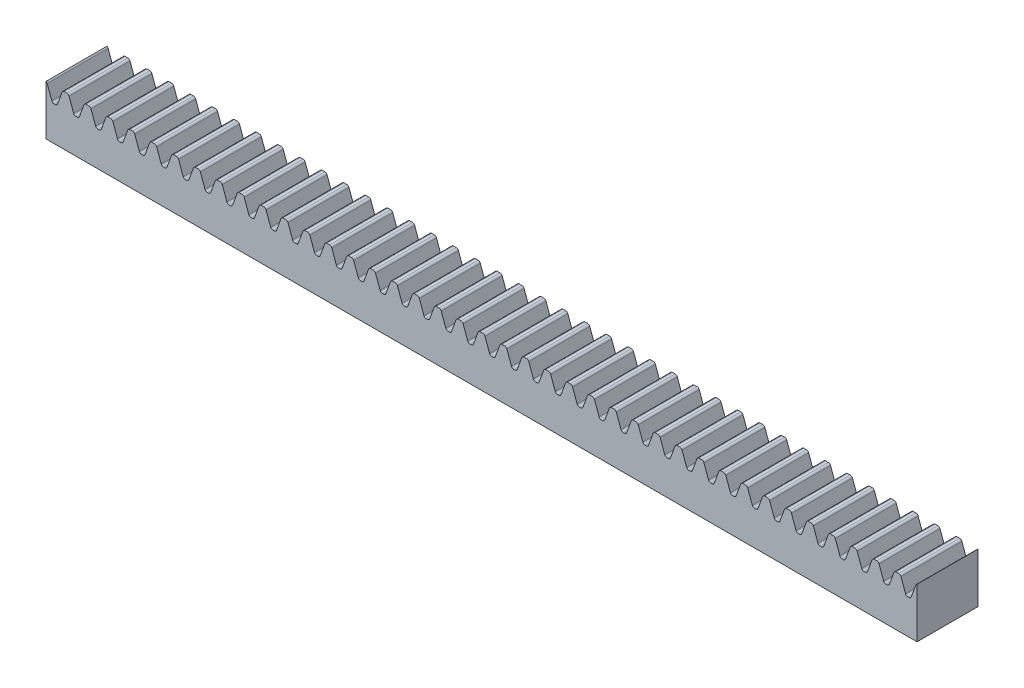
SolidWorks part; units mm, degrees
ref_plane "Front Plane" through (0, 0, 0) normal (0, 0, 1) x (1, 0, 0)
ref_plane "Top Plane" through (0, 0, 0) normal (0, 1, 0) x (1, 0, 0)
ref_plane "Right Plane" through (0, 0, 0) normal (1, 0, 0) x (0, 0, -1)
sketch "Sketch1" plane through (0, 0, 0) normal (0, 0, 1) x (1, 0, 0)
  line L0 (-50, 6.15) -> (-50, -6.15) construction
  line L1 (-50, -6.15) -> (50, -6.15) construction
  line L2 (50, -6.15) -> (50, 6.15) construction
  line L4 (0, 6.15) -> (0, -6.15) construction
  line L5 (-50, 5.35) -> (50, 5.35) construction
  line L6 (-48.0894, 6.15) -> (-47.4151, 6.15) construction
  line L7 (-47.4151, 6.15) -> (-46.7599, 4.35) construction
  line L8 (-48.0894, 6.15) -> (-48.7445, 4.35) construction
  line L9 (-48.7445, 4.35) -> (-46.7599, 4.35) construction
  line L10 (-47.7522, 6.15) -> (-47.7522, 4.35) construction
  line L11 (-50, 0) -> (-42.7257, 0) construction
  line L12 (50, 0) -> (42.7257, 0) construction
  point P15 (-45.2389, 6.15)
  point P16 (-19.5, -6.15)
  point P17 (-47.1239, 5.35)
  point P18 (-48.3805, 5.35)
  point P21 (-0.4, -6.15)
  dimension "Length" = 100
  dimension "Height" = 12.3
  dimension "Approximate Number of Teeth" = 39
  dimension "Pressure Angle" = 20
  dimension "Circular Pitch" = 2.5133
  dimension "Addendum" = 0.8
  dimension "Dedendum" = 1
  dimension "Circular Tooth Thickness" = 1.2566
  dimension "Module" = 0.8
  dimension "Rack Length" = 95.5044
  dimension "D1" = 5.0265
sketch "Sketch2" plane through (0, 0, 0) normal (1, 0, 0) x (0, 0, -1)
  line L0 (-4, 0) -> (4, 0) construction
  dimension "Face Width" = 8
sketch "Sketch3" plane through (0, 0, 0) normal (0, 0, 1) x (1, 0, 0)
  line L1 (-50, 6.15) -> (50, 6.15)
  line L2 (-50, 6.15) -> (-50, -6.15)
  line L3 (-50, -6.15) -> (50, -6.15)
  line L4 (50, 6.15) -> (50, -6.15)
extrude "Boss-Extrude1" add sketch "Sketch3" against normal up to vertex (4 mm away) and the other way up to vertex (4 mm away) up to point (0, 0, -4) other way up to point (0, 0, 4)
sketch "Sketch4" plane through (0, 0, 0) normal (0, 0, 1) x (1, 0, 0)
  line L0 (-47.7522, 6.15) -> (-45.2389, 6.15) construction
  line L9 (-46.4956, 6.15) -> (-46.4956, 4.35)
  line L10 (-46.4956, 4.35) -> (-46.7599, 4.35)
  line L11 (-46.7599, 4.35) -> (-47.4151, 6.15)
  line L12 (-47.4151, 6.15) -> (-46.4956, 6.15)
  line L13 (-48.0894, 6.15) -> (-48.7445, 4.35)
  line L14 (-48.7445, 4.35) -> (-49.0088, 4.35)
  line L15 (-49.0088, 4.35) -> (-49.0088, 6.15)
  line L16 (-49.0088, 6.15) -> (-48.0894, 6.15)
  line L17 (50, 6.15) -> (-50, 6.15) construction
  line L18 (-48.0894, 6.15) -> (-47.9014, 6.15)
  line L19 (-47.603, 6.15) -> (-47.4151, 6.15)
  arc A0 (-48.9324, 4.35) -> (-48.6802, 4.5266) centre (-48.9324, 4.6184) ccw
  arc A1 (-46.8242, 4.5266) -> (-46.572, 4.35) centre (-46.572, 4.6184) ccw
  arc A2 (-48.1536, 5.9734) -> (-47.9014, 6.15) centre (-47.9014, 5.8816) cw
  arc A3 (-47.603, 6.15) -> (-47.3508, 5.9734) centre (-47.603, 5.8816) cw
  dimension "D1" = 0.2684
extrude "Cut-Extrude1" cut sketch "Sketch4" against normal through all both and the other way through all contours L14 A0 L13 L16 L15 | L13 A2 L18 | L19 A3 L11 | L11 A1 L10 L9 L12
pattern_linear "LPattern1" count 40 spacing 2.5133 along (1, 0, 0) count 2 spacing 2.5133 along (-1, 0, 0) of "Cut-Extrude1"
sketch "Drawing Refernce 1" plane through (0, 0, 4) normal (0, 0, 1) x (1, 0, 0)
  line L0 (-50, 0) -> (50, 0) construction
  point P6 (-35, 0)
  point P7 (-27.5, 0)
  point P8 (35, 0)
  dimension "D1" = 15
  dimension "D2" = 22.5
  dimension "D3" = 15
sketch "Sketch5" plane through (0, -6.15, 0) normal (0, -1, 0) x (1, 0, 0)
  line L1 (-50, 4) -> (50, 4)
  line L2 (-50, 4) -> (-50, -4)
  line L3 (-50, -4) -> (50, -4)
  line L4 (50, 4) -> (50, -4)
extrude "Cut-Extrude2" cut sketch "Sketch5" against normal blind 6.55
sketch "Sketch6" plane through (0, 0, -4) normal (0, 0, -1) x (-1, 0, 0)
  line L162 (-50, 0.4) -> (50, 0.4)
  line L163 (50, 0.4) -> (50, 6.1235)
  line L164 (49.8641, 5.9734) -> (49.3375, 4.5266)
  line L165 (49.0853, 4.35) -> (48.9324, 4.35)
  line L166 (48.6802, 4.5266) -> (48.1536, 5.9734)
  line L167 (47.9014, 6.15) -> (47.603, 6.15)
  line L168 (47.3508, 5.9734) -> (46.8242, 4.5266)
  line L169 (46.572, 4.35) -> (46.4192, 4.35)
  line L170 (46.1669, 4.5266) -> (45.6404, 5.9734)
  line L171 (45.3881, 6.15) -> (45.0897, 6.15)
  line L172 (44.8375, 5.9734) -> (44.3109, 4.5266)
  line L173 (44.0587, 4.35) -> (43.9059, 4.35)
  line L174 (43.6537, 4.5266) -> (43.1271, 5.9734)
  line L175 (42.8749, 6.15) -> (42.5765, 6.15)
  line L176 (42.3242, 5.9734) -> (41.7977, 4.5266)
  line L177 (41.5454, 4.35) -> (41.3926, 4.35)
  line L178 (41.1404, 4.5266) -> (40.6138, 5.9734)
  line L179 (40.3616, 6.15) -> (40.0632, 6.15)
  line L180 (39.811, 5.9734) -> (39.2844, 4.5266)
  line L181 (39.0322, 4.35) -> (38.8793, 4.35)
  line L182 (38.6271, 4.5266) -> (38.1005, 5.9734)
  line L183 (37.8483, 6.15) -> (37.5499, 6.15)
  line L184 (37.2977, 5.9734) -> (36.7711, 4.5266)
  line L185 (36.5189, 4.35) -> (36.3661, 4.35)
  line L186 (36.1138, 4.5266) -> (35.5873, 5.9734)
  line L187 (35.335, 6.15) -> (35.0366, 6.15)
  line L188 (34.7844, 5.9734) -> (34.2578, 4.5266)
  line L189 (34.0056, 4.35) -> (33.8528, 4.35)
  line L190 (33.6006, 4.5266) -> (33.074, 5.9734)
  line L191 (32.8218, 6.15) -> (32.5234, 6.15)
  line L192 (32.2711, 5.9734) -> (31.7446, 4.5266)
  line L193 (31.4923, 4.35) -> (31.3395, 4.35)
  line L194 (31.0873, 4.5266) -> (30.5607, 5.9734)
  line L195 (30.3085, 6.15) -> (30.0101, 6.15)
  line L196 (29.7579, 5.9734) -> (29.2313, 4.5266)
  line L197 (28.9791, 4.35) -> (28.8262, 4.35)
  line L198 (28.574, 4.5266) -> (28.0474, 5.9734)
  line L199 (27.7952, 6.15) -> (27.4968, 6.15)
  line L200 (27.2446, 5.9734) -> (26.718, 4.5266)
  line L201 (26.4658, 4.35) -> (26.313, 4.35)
  line L202 (26.0608, 4.5266) -> (25.5342, 5.9734)
  line L203 (25.2819, 6.15) -> (24.9835, 6.15)
  line L204 (24.7313, 5.9734) -> (24.2047, 4.5266)
  line L205 (23.9525, 4.35) -> (23.7997, 4.35)
  line L206 (23.5475, 4.5266) -> (23.0209, 5.9734)
  line L207 (22.7687, 6.15) -> (22.4703, 6.15)
  line L208 (22.218, 5.9734) -> (21.6915, 4.5266)
  line L209 (21.4392, 4.35) -> (21.2864, 4.35)
  line L210 (21.0342, 4.5266) -> (20.5076, 5.9734)
  line L211 (20.2554, 6.15) -> (19.957, 6.15)
  line L212 (19.7048, 5.9734) -> (19.1782, 4.5266)
  line L213 (18.926, 4.35) -> (18.7731, 4.35)
  line L214 (18.5209, 4.5266) -> (17.9943, 5.9734)
  line L215 (17.7421, 6.15) -> (17.4437, 6.15)
  line L216 (17.1915, 5.9734) -> (16.6649, 4.5266)
  line L217 (16.4127, 4.35) -> (16.2599, 4.35)
  line L218 (16.0077, 4.5266) -> (15.4811, 5.9734)
  line L219 (15.2288, 6.15) -> (14.9304, 6.15)
  line L220 (14.6782, 5.9734) -> (14.1516, 4.5266)
  line L221 (13.8994, 4.35) -> (13.7466, 4.35)
  line L222 (13.4944, 4.5266) -> (12.9678, 5.9734)
  line L223 (12.7156, 6.15) -> (12.4172, 6.15)
  line L224 (12.1649, 5.9734) -> (11.6384, 4.5266)
  line L225 (11.3861, 4.35) -> (11.2333, 4.35)
  line L226 (10.9811, 4.5266) -> (10.4545, 5.9734)
  line L227 (10.2023, 6.15) -> (9.9039, 6.15)
  line L228 (9.6517, 5.9734) -> (9.1251, 4.5266)
  line L229 (8.8729, 4.35) -> (8.72, 4.35)
  line L230 (8.4678, 4.5266) -> (7.9412, 5.9734)
  line L231 (7.689, 6.15) -> (7.3906, 6.15)
  line L232 (7.1384, 5.9734) -> (6.6118, 4.5266)
  line L233 (6.3596, 4.35) -> (6.2068, 4.35)
  line L234 (5.9546, 4.5266) -> (5.428, 5.9734)
  line L235 (5.1758, 6.15) -> (4.8773, 6.15)
  line L236 (4.6251, 5.9734) -> (4.0985, 4.5266)
  line L237 (3.8463, 4.35) -> (3.6935, 4.35)
  line L238 (3.4413, 4.5266) -> (2.9147, 5.9734)
  line L239 (2.6625, 6.15) -> (2.3641, 6.15)
  line L240 (2.1119, 5.9734) -> (1.5853, 4.5266)
  line L241 (1.333, 4.35) -> (1.1802, 4.35)
  line L242 (0.928, 4.5266) -> (0.4014, 5.9734)
  line L243 (0.1492, 6.15) -> (-0.1492, 6.15)
  line L244 (-0.4014, 5.9734) -> (-0.928, 4.5266)
  line L245 (-1.1802, 4.35) -> (-1.333, 4.35)
  line L246 (-1.5853, 4.5266) -> (-2.1119, 5.9734)
  line L247 (-2.3641, 6.15) -> (-2.6625, 6.15)
  line L248 (-2.9147, 5.9734) -> (-3.4413, 4.5266)
  line L249 (-3.6935, 4.35) -> (-3.8463, 4.35)
  line L250 (-4.0985, 4.5266) -> (-4.6251, 5.9734)
  line L251 (-4.8773, 6.15) -> (-5.1758, 6.15)
  line L252 (-5.428, 5.9734) -> (-5.9546, 4.5266)
  line L253 (-6.2068, 4.35) -> (-6.3596, 4.35)
  line L254 (-6.6118, 4.5266) -> (-7.1384, 5.9734)
  line L255 (-7.3906, 6.15) -> (-7.689, 6.15)
  line L256 (-7.9412, 5.9734) -> (-8.4678, 4.5266)
  line L257 (-8.72, 4.35) -> (-8.8729, 4.35)
  line L258 (-9.1251, 4.5266) -> (-9.6517, 5.9734)
  line L259 (-9.9039, 6.15) -> (-10.2023, 6.15)
  line L260 (-10.4545, 5.9734) -> (-10.9811, 4.5266)
  line L261 (-11.2333, 4.35) -> (-11.3861, 4.35)
  line L262 (-11.6384, 4.5266) -> (-12.1649, 5.9734)
  line L263 (-12.4172, 6.15) -> (-12.7156, 6.15)
  line L264 (-12.9678, 5.9734) -> (-13.4944, 4.5266)
  line L265 (-13.7466, 4.35) -> (-13.8994, 4.35)
  line L266 (-14.1516, 4.5266) -> (-14.6782, 5.9734)
  line L267 (-14.9304, 6.15) -> (-15.2288, 6.15)
  line L268 (-15.4811, 5.9734) -> (-16.0077, 4.5266)
  line L269 (-16.2599, 4.35) -> (-16.4127, 4.35)
  line L270 (-16.6649, 4.5266) -> (-17.1915, 5.9734)
  line L271 (-17.4437, 6.15) -> (-17.7421, 6.15)
  line L272 (-17.9943, 5.9734) -> (-18.5209, 4.5266)
  line L273 (-18.7731, 4.35) -> (-18.926, 4.35)
  line L274 (-19.1782, 4.5266) -> (-19.7048, 5.9734)
  line L275 (-19.957, 6.15) -> (-20.2554, 6.15)
  line L276 (-20.5076, 5.9734) -> (-21.0342, 4.5266)
  line L277 (-21.2864, 4.35) -> (-21.4392, 4.35)
  line L278 (-21.6915, 4.5266) -> (-22.218, 5.9734)
  line L279 (-22.4703, 6.15) -> (-22.7687, 6.15)
  line L280 (-23.0209, 5.9734) -> (-23.5475, 4.5266)
  line L281 (-23.7997, 4.35) -> (-23.9525, 4.35)
  line L282 (-24.2047, 4.5266) -> (-24.7313, 5.9734)
  line L283 (-24.9835, 6.15) -> (-25.2819, 6.15)
  line L284 (-25.5342, 5.9734) -> (-26.0608, 4.5266)
  line L285 (-26.313, 4.35) -> (-26.4658, 4.35)
  line L286 (-26.718, 4.5266) -> (-27.2446, 5.9734)
  line L287 (-27.4968, 6.15) -> (-27.7952, 6.15)
  line L288 (-28.0474, 5.9734) -> (-28.574, 4.5266)
  line L289 (-28.8262, 4.35) -> (-28.9791, 4.35)
  line L290 (-29.2313, 4.5266) -> (-29.7579, 5.9734)
  line L291 (-30.0101, 6.15) -> (-30.3085, 6.15)
  line L292 (-30.5607, 5.9734) -> (-31.0873, 4.5266)
  line L293 (-31.3395, 4.35) -> (-31.4923, 4.35)
  line L294 (-31.7446, 4.5266) -> (-32.2711, 5.9734)
  line L295 (-32.5234, 6.15) -> (-32.8218, 6.15)
  line L296 (-33.074, 5.9734) -> (-33.6006, 4.5266)
  line L297 (-33.8528, 4.35) -> (-34.0056, 4.35)
  line L298 (-34.2578, 4.5266) -> (-34.7844, 5.9734)
  line L299 (-35.0366, 6.15) -> (-35.335, 6.15)
  line L300 (-35.5873, 5.9734) -> (-36.1138, 4.5266)
  line L301 (-36.3661, 4.35) -> (-36.5189, 4.35)
  line L302 (-36.7711, 4.5266) -> (-37.2977, 5.9734)
  line L303 (-37.5499, 6.15) -> (-37.8483, 6.15)
  line L304 (-38.1005, 5.9734) -> (-38.6271, 4.5266)
  line L305 (-38.8793, 4.35) -> (-39.0322, 4.35)
  line L306 (-39.2844, 4.5266) -> (-39.811, 5.9734)
  line L307 (-40.0632, 6.15) -> (-40.3616, 6.15)
  line L308 (-40.6138, 5.9734) -> (-41.1404, 4.5266)
  line L309 (-41.3926, 4.35) -> (-41.5454, 4.35)
  line L310 (-41.7977, 4.5266) -> (-42.3242, 5.9734)
  line L311 (-42.5765, 6.15) -> (-42.8749, 6.15)
  line L312 (-43.1271, 5.9734) -> (-43.6537, 4.5266)
  line L313 (-43.9059, 4.35) -> (-44.0587, 4.35)
  line L314 (-44.3109, 4.5266) -> (-44.8375, 5.9734)
  line L315 (-45.0897, 6.15) -> (-45.3881, 6.15)
  line L316 (-45.6404, 5.9734) -> (-46.1669, 4.5266)
  line L317 (-46.4192, 4.35) -> (-46.572, 4.35)
  line L318 (-46.8242, 4.5266) -> (-47.3508, 5.9734)
  line L319 (-47.603, 6.15) -> (-47.9014, 6.15)
  line L320 (-48.1536, 5.9734) -> (-48.6802, 4.5266)
  line L321 (-48.9324, 4.35) -> (-49.0853, 4.35)
  line L322 (-49.3375, 4.5266) -> (-49.8641, 5.9734)
  line L323 (-50, 6.1235) -> (-50, 0.4)
  line L324 (-50, 0.4) -> (50, 0.4)
  line L325 (50, 0.4) -> (50, 6.1235)
  line L326 (49.8641, 5.9734) -> (49.3375, 4.5266)
  line L327 (49.0853, 4.35) -> (48.9324, 4.35)
  line L328 (48.6802, 4.5266) -> (48.1536, 5.9734)
  line L329 (47.9014, 6.15) -> (47.603, 6.15)
  line L330 (47.3508, 5.9734) -> (46.8242, 4.5266)
  line L331 (46.572, 4.35) -> (46.4192, 4.35)
  line L332 (46.1669, 4.5266) -> (45.6404, 5.9734)
  line L333 (45.3881, 6.15) -> (45.0897, 6.15)
  line L334 (44.8375, 5.9734) -> (44.3109, 4.5266)
  line L335 (44.0587, 4.35) -> (43.9059, 4.35)
  line L336 (43.6537, 4.5266) -> (43.1271, 5.9734)
  line L337 (42.8749, 6.15) -> (42.5765, 6.15)
  line L338 (42.3242, 5.9734) -> (41.7977, 4.5266)
  line L339 (41.5454, 4.35) -> (41.3926, 4.35)
  line L340 (41.1404, 4.5266) -> (40.6138, 5.9734)
  line L341 (40.3616, 6.15) -> (40.0632, 6.15)
  line L342 (39.811, 5.9734) -> (39.2844, 4.5266)
  line L343 (39.0322, 4.35) -> (38.8793, 4.35)
  line L344 (38.6271, 4.5266) -> (38.1005, 5.9734)
  line L345 (37.8483, 6.15) -> (37.5499, 6.15)
  line L346 (37.2977, 5.9734) -> (36.7711, 4.5266)
  line L347 (36.5189, 4.35) -> (36.3661, 4.35)
  line L348 (36.1138, 4.5266) -> (35.5873, 5.9734)
  line L349 (35.335, 6.15) -> (35.0366, 6.15)
  line L350 (34.7844, 5.9734) -> (34.2578, 4.5266)
  line L351 (34.0056, 4.35) -> (33.8528, 4.35)
  line L352 (33.6006, 4.5266) -> (33.074, 5.9734)
  line L353 (32.8218, 6.15) -> (32.5234, 6.15)
  line L354 (32.2711, 5.9734) -> (31.7446, 4.5266)
  line L355 (31.4923, 4.35) -> (31.3395, 4.35)
  line L356 (31.0873, 4.5266) -> (30.5607, 5.9734)
  line L357 (30.3085, 6.15) -> (30.0101, 6.15)
  line L358 (29.7579, 5.9734) -> (29.2313, 4.5266)
  line L359 (28.9791, 4.35) -> (28.8262, 4.35)
  line L360 (28.574, 4.5266) -> (28.0474, 5.9734)
  line L361 (27.7952, 6.15) -> (27.4968, 6.15)
  line L362 (27.2446, 5.9734) -> (26.718, 4.5266)
  line L363 (26.4658, 4.35) -> (26.313, 4.35)
  line L364 (26.0608, 4.5266) -> (25.5342, 5.9734)
  line L365 (25.2819, 6.15) -> (24.9835, 6.15)
  line L366 (24.7313, 5.9734) -> (24.2047, 4.5266)
  line L367 (23.9525, 4.35) -> (23.7997, 4.35)
  line L368 (23.5475, 4.5266) -> (23.0209, 5.9734)
  line L369 (22.7687, 6.15) -> (22.4703, 6.15)
  line L370 (22.218, 5.9734) -> (21.6915, 4.5266)
  line L371 (21.4392, 4.35) -> (21.2864, 4.35)
  line L372 (21.0342, 4.5266) -> (20.5076, 5.9734)
  line L373 (20.2554, 6.15) -> (19.957, 6.15)
  line L374 (19.7048, 5.9734) -> (19.1782, 4.5266)
  line L375 (18.926, 4.35) -> (18.7731, 4.35)
  line L376 (18.5209, 4.5266) -> (17.9943, 5.9734)
  line L377 (17.7421, 6.15) -> (17.4437, 6.15)
  line L378 (17.1915, 5.9734) -> (16.6649, 4.5266)
  line L379 (16.4127, 4.35) -> (16.2599, 4.35)
  line L380 (16.0077, 4.5266) -> (15.4811, 5.9734)
  line L381 (15.2288, 6.15) -> (14.9304, 6.15)
  line L382 (14.6782, 5.9734) -> (14.1516, 4.5266)
  line L383 (13.8994, 4.35) -> (13.7466, 4.35)
  line L384 (13.4944, 4.5266) -> (12.9678, 5.9734)
  line L385 (12.7156, 6.15) -> (12.4172, 6.15)
  line L386 (12.1649, 5.9734) -> (11.6384, 4.5266)
  line L387 (11.3861, 4.35) -> (11.2333, 4.35)
  line L388 (10.9811, 4.5266) -> (10.4545, 5.9734)
  line L389 (10.2023, 6.15) -> (9.9039, 6.15)
  line L390 (9.6517, 5.9734) -> (9.1251, 4.5266)
  line L391 (8.8729, 4.35) -> (8.72, 4.35)
  line L392 (8.4678, 4.5266) -> (7.9412, 5.9734)
  line L393 (7.689, 6.15) -> (7.3906, 6.15)
  line L394 (7.1384, 5.9734) -> (6.6118, 4.5266)
  line L395 (6.3596, 4.35) -> (6.2068, 4.35)
  line L396 (5.9546, 4.5266) -> (5.428, 5.9734)
  line L397 (5.1758, 6.15) -> (4.8773, 6.15)
  line L398 (4.6251, 5.9734) -> (4.0985, 4.5266)
  line L399 (3.8463, 4.35) -> (3.6935, 4.35)
  line L400 (3.4413, 4.5266) -> (2.9147, 5.9734)
  line L401 (2.6625, 6.15) -> (2.3641, 6.15)
  line L402 (2.1119, 5.9734) -> (1.5853, 4.5266)
  line L403 (1.333, 4.35) -> (1.1802, 4.35)
  line L404 (0.928, 4.5266) -> (0.4014, 5.9734)
  line L405 (0.1492, 6.15) -> (-0.1492, 6.15)
  line L406 (-0.4014, 5.9734) -> (-0.928, 4.5266)
  line L407 (-1.1802, 4.35) -> (-1.333, 4.35)
  line L408 (-1.5853, 4.5266) -> (-2.1119, 5.9734)
  line L409 (-2.3641, 6.15) -> (-2.6625, 6.15)
  line L410 (-2.9147, 5.9734) -> (-3.4413, 4.5266)
  line L411 (-3.6935, 4.35) -> (-3.8463, 4.35)
  line L412 (-4.0985, 4.5266) -> (-4.6251, 5.9734)
  line L413 (-4.8773, 6.15) -> (-5.1758, 6.15)
  line L414 (-5.428, 5.9734) -> (-5.9546, 4.5266)
  line L415 (-6.2068, 4.35) -> (-6.3596, 4.35)
  line L416 (-6.6118, 4.5266) -> (-7.1384, 5.9734)
  line L417 (-7.3906, 6.15) -> (-7.689, 6.15)
  line L418 (-7.9412, 5.9734) -> (-8.4678, 4.5266)
  line L419 (-8.72, 4.35) -> (-8.8729, 4.35)
  line L420 (-9.1251, 4.5266) -> (-9.6517, 5.9734)
  line L421 (-9.9039, 6.15) -> (-10.2023, 6.15)
  line L422 (-10.4545, 5.9734) -> (-10.9811, 4.5266)
  line L423 (-11.2333, 4.35) -> (-11.3861, 4.35)
  line L424 (-11.6384, 4.5266) -> (-12.1649, 5.9734)
  line L425 (-12.4172, 6.15) -> (-12.7156, 6.15)
  line L426 (-12.9678, 5.9734) -> (-13.4944, 4.5266)
  line L427 (-13.7466, 4.35) -> (-13.8994, 4.35)
  line L428 (-14.1516, 4.5266) -> (-14.6782, 5.9734)
  line L429 (-14.9304, 6.15) -> (-15.2288, 6.15)
  line L430 (-15.4811, 5.9734) -> (-16.0077, 4.5266)
  line L431 (-16.2599, 4.35) -> (-16.4127, 4.35)
  line L432 (-16.6649, 4.5266) -> (-17.1915, 5.9734)
  line L433 (-17.4437, 6.15) -> (-17.7421, 6.15)
  line L434 (-17.9943, 5.9734) -> (-18.5209, 4.5266)
  line L435 (-18.7731, 4.35) -> (-18.926, 4.35)
  line L436 (-19.1782, 4.5266) -> (-19.7048, 5.9734)
  line L437 (-19.957, 6.15) -> (-20.2554, 6.15)
  line L438 (-20.5076, 5.9734) -> (-21.0342, 4.5266)
  line L439 (-21.2864, 4.35) -> (-21.4392, 4.35)
  line L440 (-21.6915, 4.5266) -> (-22.218, 5.9734)
  line L441 (-22.4703, 6.15) -> (-22.7687, 6.15)
  line L442 (-23.0209, 5.9734) -> (-23.5475, 4.5266)
  line L443 (-23.7997, 4.35) -> (-23.9525, 4.35)
  line L444 (-24.2047, 4.5266) -> (-24.7313, 5.9734)
  line L445 (-24.9835, 6.15) -> (-25.2819, 6.15)
  line L446 (-25.5342, 5.9734) -> (-26.0608, 4.5266)
  line L447 (-26.313, 4.35) -> (-26.4658, 4.35)
  line L448 (-26.718, 4.5266) -> (-27.2446, 5.9734)
  line L449 (-27.4968, 6.15) -> (-27.7952, 6.15)
  line L450 (-28.0474, 5.9734) -> (-28.574, 4.5266)
  line L451 (-28.8262, 4.35) -> (-28.9791, 4.35)
  line L452 (-29.2313, 4.5266) -> (-29.7579, 5.9734)
  line L453 (-30.0101, 6.15) -> (-30.3085, 6.15)
  line L454 (-30.5607, 5.9734) -> (-31.0873, 4.5266)
  line L455 (-31.3395, 4.35) -> (-31.4923, 4.35)
  line L456 (-31.7446, 4.5266) -> (-32.2711, 5.9734)
  line L457 (-32.5234, 6.15) -> (-32.8218, 6.15)
  line L458 (-33.074, 5.9734) -> (-33.6006, 4.5266)
  line L459 (-33.8528, 4.35) -> (-34.0056, 4.35)
  line L460 (-34.2578, 4.5266) -> (-34.7844, 5.9734)
  line L461 (-35.0366, 6.15) -> (-35.335, 6.15)
  line L462 (-35.5873, 5.9734) -> (-36.1138, 4.5266)
  line L463 (-36.3661, 4.35) -> (-36.5189, 4.35)
  line L464 (-36.7711, 4.5266) -> (-37.2977, 5.9734)
  line L465 (-37.5499, 6.15) -> (-37.8483, 6.15)
  line L466 (-38.1005, 5.9734) -> (-38.6271, 4.5266)
  line L467 (-38.8793, 4.35) -> (-39.0322, 4.35)
  line L468 (-39.2844, 4.5266) -> (-39.811, 5.9734)
  line L469 (-40.0632, 6.15) -> (-40.3616, 6.15)
  line L470 (-40.6138, 5.9734) -> (-41.1404, 4.5266)
  line L471 (-41.3926, 4.35) -> (-41.5454, 4.35)
  line L472 (-41.7977, 4.5266) -> (-42.3242, 5.9734)
  line L473 (-42.5765, 6.15) -> (-42.8749, 6.15)
  line L474 (-43.1271, 5.9734) -> (-43.6537, 4.5266)
  line L475 (-43.9059, 4.35) -> (-44.0587, 4.35)
  line L476 (-44.3109, 4.5266) -> (-44.8375, 5.9734)
  line L477 (-45.0897, 6.15) -> (-45.3881, 6.15)
  line L478 (-45.6404, 5.9734) -> (-46.1669, 4.5266)
  line L479 (-46.4192, 4.35) -> (-46.572, 4.35)
  line L480 (-46.8242, 4.5266) -> (-47.3508, 5.9734)
  line L481 (-47.603, 6.15) -> (-47.9014, 6.15)
  line L482 (-48.1536, 5.9734) -> (-48.6802, 4.5266)
  line L483 (-48.9324, 4.35) -> (-49.0853, 4.35)
  line L484 (-49.3375, 4.5266) -> (-49.8641, 5.9734)
  line L485 (-50, 6.1235) -> (-50, 0.4)
  arc A160 (50, 6.1235) -> (49.8641, 5.9734) centre (50.1163, 5.8816) ccw
  arc A161 (49.0853, 4.35) -> (49.3375, 4.5266) centre (49.0853, 4.6184) ccw
  arc A162 (48.6802, 4.5266) -> (48.9324, 4.35) centre (48.9324, 4.6184) ccw
  arc A163 (48.1536, 5.9734) -> (47.9014, 6.15) centre (47.9014, 5.8816) ccw
  arc A164 (47.603, 6.15) -> (47.3508, 5.9734) centre (47.603, 5.8816) ccw
  arc A165 (46.572, 4.35) -> (46.8242, 4.5266) centre (46.572, 4.6184) ccw
  arc A166 (46.1669, 4.5266) -> (46.4192, 4.35) centre (46.4192, 4.6184) ccw
  arc A167 (45.6404, 5.9734) -> (45.3881, 6.15) centre (45.3881, 5.8816) ccw
  arc A168 (45.0897, 6.15) -> (44.8375, 5.9734) centre (45.0897, 5.8816) ccw
  arc A169 (44.0587, 4.35) -> (44.3109, 4.5266) centre (44.0587, 4.6184) ccw
  arc A170 (43.6537, 4.5266) -> (43.9059, 4.35) centre (43.9059, 4.6184) ccw
  arc A171 (43.1271, 5.9734) -> (42.8749, 6.15) centre (42.8749, 5.8816) ccw
  arc A172 (42.5765, 6.15) -> (42.3242, 5.9734) centre (42.5765, 5.8816) ccw
  arc A173 (41.5454, 4.35) -> (41.7977, 4.5266) centre (41.5454, 4.6184) ccw
  arc A174 (41.1404, 4.5266) -> (41.3926, 4.35) centre (41.3926, 4.6184) ccw
  arc A175 (40.6138, 5.9734) -> (40.3616, 6.15) centre (40.3616, 5.8816) ccw
  arc A176 (40.0632, 6.15) -> (39.811, 5.9734) centre (40.0632, 5.8816) ccw
  arc A177 (39.0322, 4.35) -> (39.2844, 4.5266) centre (39.0322, 4.6184) ccw
  arc A178 (38.6271, 4.5266) -> (38.8793, 4.35) centre (38.8793, 4.6184) ccw
  arc A179 (38.1005, 5.9734) -> (37.8483, 6.15) centre (37.8483, 5.8816) ccw
  arc A180 (37.5499, 6.15) -> (37.2977, 5.9734) centre (37.5499, 5.8816) ccw
  arc A181 (36.5189, 4.35) -> (36.7711, 4.5266) centre (36.5189, 4.6184) ccw
  arc A182 (36.1138, 4.5266) -> (36.3661, 4.35) centre (36.3661, 4.6184) ccw
  arc A183 (35.5873, 5.9734) -> (35.335, 6.15) centre (35.335, 5.8816) ccw
  arc A184 (35.0366, 6.15) -> (34.7844, 5.9734) centre (35.0366, 5.8816) ccw
  arc A185 (34.0056, 4.35) -> (34.2578, 4.5266) centre (34.0056, 4.6184) ccw
  arc A186 (33.6006, 4.5266) -> (33.8528, 4.35) centre (33.8528, 4.6184) ccw
  arc A187 (33.074, 5.9734) -> (32.8218, 6.15) centre (32.8218, 5.8816) ccw
  arc A188 (32.5234, 6.15) -> (32.2711, 5.9734) centre (32.5234, 5.8816) ccw
  arc A189 (31.4923, 4.35) -> (31.7446, 4.5266) centre (31.4923, 4.6184) ccw
  arc A190 (31.0873, 4.5266) -> (31.3395, 4.35) centre (31.3395, 4.6184) ccw
  arc A191 (30.5607, 5.9734) -> (30.3085, 6.15) centre (30.3085, 5.8816) ccw
  arc A192 (30.0101, 6.15) -> (29.7579, 5.9734) centre (30.0101, 5.8816) ccw
  arc A193 (28.9791, 4.35) -> (29.2313, 4.5266) centre (28.9791, 4.6184) ccw
  arc A194 (28.574, 4.5266) -> (28.8262, 4.35) centre (28.8262, 4.6184) ccw
  arc A195 (28.0474, 5.9734) -> (27.7952, 6.15) centre (27.7952, 5.8816) ccw
  arc A196 (27.4968, 6.15) -> (27.2446, 5.9734) centre (27.4968, 5.8816) ccw
  arc A197 (26.4658, 4.35) -> (26.718, 4.5266) centre (26.4658, 4.6184) ccw
  arc A198 (26.0608, 4.5266) -> (26.313, 4.35) centre (26.313, 4.6184) ccw
  arc A199 (25.5342, 5.9734) -> (25.2819, 6.15) centre (25.2819, 5.8816) ccw
  arc A200 (24.9835, 6.15) -> (24.7313, 5.9734) centre (24.9835, 5.8816) ccw
  arc A201 (23.9525, 4.35) -> (24.2047, 4.5266) centre (23.9525, 4.6184) ccw
  arc A202 (23.5475, 4.5266) -> (23.7997, 4.35) centre (23.7997, 4.6184) ccw
  arc A203 (23.0209, 5.9734) -> (22.7687, 6.15) centre (22.7687, 5.8816) ccw
  arc A204 (22.4703, 6.15) -> (22.218, 5.9734) centre (22.4703, 5.8816) ccw
  arc A205 (21.4392, 4.35) -> (21.6915, 4.5266) centre (21.4392, 4.6184) ccw
  arc A206 (21.0342, 4.5266) -> (21.2864, 4.35) centre (21.2864, 4.6184) ccw
  arc A207 (20.5076, 5.9734) -> (20.2554, 6.15) centre (20.2554, 5.8816) ccw
  arc A208 (19.957, 6.15) -> (19.7048, 5.9734) centre (19.957, 5.8816) ccw
  arc A209 (18.926, 4.35) -> (19.1782, 4.5266) centre (18.926, 4.6184) ccw
  arc A210 (18.5209, 4.5266) -> (18.7731, 4.35) centre (18.7731, 4.6184) ccw
  arc A211 (17.9943, 5.9734) -> (17.7421, 6.15) centre (17.7421, 5.8816) ccw
  arc A212 (17.4437, 6.15) -> (17.1915, 5.9734) centre (17.4437, 5.8816) ccw
  arc A213 (16.4127, 4.35) -> (16.6649, 4.5266) centre (16.4127, 4.6184) ccw
  arc A214 (16.0077, 4.5266) -> (16.2599, 4.35) centre (16.2599, 4.6184) ccw
  arc A215 (15.4811, 5.9734) -> (15.2288, 6.15) centre (15.2288, 5.8816) ccw
  arc A216 (14.9304, 6.15) -> (14.6782, 5.9734) centre (14.9304, 5.8816) ccw
  arc A217 (13.8994, 4.35) -> (14.1516, 4.5266) centre (13.8994, 4.6184) ccw
  arc A218 (13.4944, 4.5266) -> (13.7466, 4.35) centre (13.7466, 4.6184) ccw
  arc A219 (12.9678, 5.9734) -> (12.7156, 6.15) centre (12.7156, 5.8816) ccw
  arc A220 (12.4172, 6.15) -> (12.1649, 5.9734) centre (12.4172, 5.8816) ccw
  arc A221 (11.3861, 4.35) -> (11.6384, 4.5266) centre (11.3861, 4.6184) ccw
  arc A222 (10.9811, 4.5266) -> (11.2333, 4.35) centre (11.2333, 4.6184) ccw
  arc A223 (10.4545, 5.9734) -> (10.2023, 6.15) centre (10.2023, 5.8816) ccw
  arc A224 (9.9039, 6.15) -> (9.6517, 5.9734) centre (9.9039, 5.8816) ccw
  arc A225 (8.8729, 4.35) -> (9.1251, 4.5266) centre (8.8729, 4.6184) ccw
  arc A226 (8.4678, 4.5266) -> (8.72, 4.35) centre (8.72, 4.6184) ccw
  arc A227 (7.9412, 5.9734) -> (7.689, 6.15) centre (7.689, 5.8816) ccw
  arc A228 (7.3906, 6.15) -> (7.1384, 5.9734) centre (7.3906, 5.8816) ccw
  arc A229 (6.3596, 4.35) -> (6.6118, 4.5266) centre (6.3596, 4.6184) ccw
  arc A230 (5.9546, 4.5266) -> (6.2068, 4.35) centre (6.2068, 4.6184) ccw
  arc A231 (5.428, 5.9734) -> (5.1758, 6.15) centre (5.1758, 5.8816) ccw
  arc A232 (4.8773, 6.15) -> (4.6251, 5.9734) centre (4.8773, 5.8816) ccw
  arc A233 (3.8463, 4.35) -> (4.0985, 4.5266) centre (3.8463, 4.6184) ccw
  arc A234 (3.4413, 4.5266) -> (3.6935, 4.35) centre (3.6935, 4.6184) ccw
  arc A235 (2.9147, 5.9734) -> (2.6625, 6.15) centre (2.6625, 5.8816) ccw
  arc A236 (2.3641, 6.15) -> (2.1119, 5.9734) centre (2.3641, 5.8816) ccw
  arc A237 (1.333, 4.35) -> (1.5853, 4.5266) centre (1.333, 4.6184) ccw
  arc A238 (0.928, 4.5266) -> (1.1802, 4.35) centre (1.1802, 4.6184) ccw
  arc A239 (0.4014, 5.9734) -> (0.1492, 6.15) centre (0.1492, 5.8816) ccw
  arc A240 (-0.1492, 6.15) -> (-0.4014, 5.9734) centre (-0.1492, 5.8816) ccw
  arc A241 (-1.1802, 4.35) -> (-0.928, 4.5266) centre (-1.1802, 4.6184) ccw
  arc A242 (-1.5853, 4.5266) -> (-1.333, 4.35) centre (-1.333, 4.6184) ccw
  arc A243 (-2.1119, 5.9734) -> (-2.3641, 6.15) centre (-2.3641, 5.8816) ccw
  arc A244 (-2.6625, 6.15) -> (-2.9147, 5.9734) centre (-2.6625, 5.8816) ccw
  arc A245 (-3.6935, 4.35) -> (-3.4413, 4.5266) centre (-3.6935, 4.6184) ccw
  arc A246 (-4.0985, 4.5266) -> (-3.8463, 4.35) centre (-3.8463, 4.6184) ccw
  arc A247 (-4.6251, 5.9734) -> (-4.8773, 6.15) centre (-4.8773, 5.8816) ccw
  arc A248 (-5.1758, 6.15) -> (-5.428, 5.9734) centre (-5.1758, 5.8816) ccw
  arc A249 (-6.2068, 4.35) -> (-5.9546, 4.5266) centre (-6.2068, 4.6184) ccw
  arc A250 (-6.6118, 4.5266) -> (-6.3596, 4.35) centre (-6.3596, 4.6184) ccw
  arc A251 (-7.1384, 5.9734) -> (-7.3906, 6.15) centre (-7.3906, 5.8816) ccw
  arc A252 (-7.689, 6.15) -> (-7.9412, 5.9734) centre (-7.689, 5.8816) ccw
  arc A253 (-8.72, 4.35) -> (-8.4678, 4.5266) centre (-8.72, 4.6184) ccw
  arc A254 (-9.1251, 4.5266) -> (-8.8729, 4.35) centre (-8.8729, 4.6184) ccw
  arc A255 (-9.6517, 5.9734) -> (-9.9039, 6.15) centre (-9.9039, 5.8816) ccw
  arc A256 (-10.2023, 6.15) -> (-10.4545, 5.9734) centre (-10.2023, 5.8816) ccw
  arc A257 (-11.2333, 4.35) -> (-10.9811, 4.5266) centre (-11.2333, 4.6184) ccw
  arc A258 (-11.6384, 4.5266) -> (-11.3861, 4.35) centre (-11.3861, 4.6184) ccw
  arc A259 (-12.1649, 5.9734) -> (-12.4172, 6.15) centre (-12.4172, 5.8816) ccw
  arc A260 (-12.7156, 6.15) -> (-12.9678, 5.9734) centre (-12.7156, 5.8816) ccw
  arc A261 (-13.7466, 4.35) -> (-13.4944, 4.5266) centre (-13.7466, 4.6184) ccw
  arc A262 (-14.1516, 4.5266) -> (-13.8994, 4.35) centre (-13.8994, 4.6184) ccw
  arc A263 (-14.6782, 5.9734) -> (-14.9304, 6.15) centre (-14.9304, 5.8816) ccw
  arc A264 (-15.2288, 6.15) -> (-15.4811, 5.9734) centre (-15.2288, 5.8816) ccw
  arc A265 (-16.2599, 4.35) -> (-16.0077, 4.5266) centre (-16.2599, 4.6184) ccw
  arc A266 (-16.6649, 4.5266) -> (-16.4127, 4.35) centre (-16.4127, 4.6184) ccw
  arc A267 (-17.1915, 5.9734) -> (-17.4437, 6.15) centre (-17.4437, 5.8816) ccw
  arc A268 (-17.7421, 6.15) -> (-17.9943, 5.9734) centre (-17.7421, 5.8816) ccw
  arc A269 (-18.7731, 4.35) -> (-18.5209, 4.5266) centre (-18.7731, 4.6184) ccw
  arc A270 (-19.1782, 4.5266) -> (-18.926, 4.35) centre (-18.926, 4.6184) ccw
  arc A271 (-19.7048, 5.9734) -> (-19.957, 6.15) centre (-19.957, 5.8816) ccw
  arc A272 (-20.2554, 6.15) -> (-20.5076, 5.9734) centre (-20.2554, 5.8816) ccw
  arc A273 (-21.2864, 4.35) -> (-21.0342, 4.5266) centre (-21.2864, 4.6184) ccw
  arc A274 (-21.6915, 4.5266) -> (-21.4392, 4.35) centre (-21.4392, 4.6184) ccw
  arc A275 (-22.218, 5.9734) -> (-22.4703, 6.15) centre (-22.4703, 5.8816) ccw
  arc A276 (-22.7687, 6.15) -> (-23.0209, 5.9734) centre (-22.7687, 5.8816) ccw
  arc A277 (-23.7997, 4.35) -> (-23.5475, 4.5266) centre (-23.7997, 4.6184) ccw
  arc A278 (-24.2047, 4.5266) -> (-23.9525, 4.35) centre (-23.9525, 4.6184) ccw
  arc A279 (-24.7313, 5.9734) -> (-24.9835, 6.15) centre (-24.9835, 5.8816) ccw
  arc A280 (-25.2819, 6.15) -> (-25.5342, 5.9734) centre (-25.2819, 5.8816) ccw
  arc A281 (-26.313, 4.35) -> (-26.0608, 4.5266) centre (-26.313, 4.6184) ccw
  arc A282 (-26.718, 4.5266) -> (-26.4658, 4.35) centre (-26.4658, 4.6184) ccw
  arc A283 (-27.2446, 5.9734) -> (-27.4968, 6.15) centre (-27.4968, 5.8816) ccw
  arc A284 (-27.7952, 6.15) -> (-28.0474, 5.9734) centre (-27.7952, 5.8816) ccw
  arc A285 (-28.8262, 4.35) -> (-28.574, 4.5266) centre (-28.8262, 4.6184) ccw
  arc A286 (-29.2313, 4.5266) -> (-28.9791, 4.35) centre (-28.9791, 4.6184) ccw
  arc A287 (-29.7579, 5.9734) -> (-30.0101, 6.15) centre (-30.0101, 5.8816) ccw
  arc A288 (-30.3085, 6.15) -> (-30.5607, 5.9734) centre (-30.3085, 5.8816) ccw
  arc A289 (-31.3395, 4.35) -> (-31.0873, 4.5266) centre (-31.3395, 4.6184) ccw
  arc A290 (-31.7446, 4.5266) -> (-31.4923, 4.35) centre (-31.4923, 4.6184) ccw
  arc A291 (-32.2711, 5.9734) -> (-32.5234, 6.15) centre (-32.5234, 5.8816) ccw
  arc A292 (-32.8218, 6.15) -> (-33.074, 5.9734) centre (-32.8218, 5.8816) ccw
  arc A293 (-33.8528, 4.35) -> (-33.6006, 4.5266) centre (-33.8528, 4.6184) ccw
  arc A294 (-34.2578, 4.5266) -> (-34.0056, 4.35) centre (-34.0056, 4.6184) ccw
  arc A295 (-34.7844, 5.9734) -> (-35.0366, 6.15) centre (-35.0366, 5.8816) ccw
  arc A296 (-35.335, 6.15) -> (-35.5873, 5.9734) centre (-35.335, 5.8816) ccw
  arc A297 (-36.3661, 4.35) -> (-36.1138, 4.5266) centre (-36.3661, 4.6184) ccw
  arc A298 (-36.7711, 4.5266) -> (-36.5189, 4.35) centre (-36.5189, 4.6184) ccw
  arc A299 (-37.2977, 5.9734) -> (-37.5499, 6.15) centre (-37.5499, 5.8816) ccw
  arc A300 (-37.8483, 6.15) -> (-38.1005, 5.9734) centre (-37.8483, 5.8816) ccw
  arc A301 (-38.8793, 4.35) -> (-38.6271, 4.5266) centre (-38.8793, 4.6184) ccw
  arc A302 (-39.2844, 4.5266) -> (-39.0322, 4.35) centre (-39.0322, 4.6184) ccw
  arc A303 (-39.811, 5.9734) -> (-40.0632, 6.15) centre (-40.0632, 5.8816) ccw
  arc A304 (-40.3616, 6.15) -> (-40.6138, 5.9734) centre (-40.3616, 5.8816) ccw
  arc A305 (-41.3926, 4.35) -> (-41.1404, 4.5266) centre (-41.3926, 4.6184) ccw
  arc A306 (-41.7977, 4.5266) -> (-41.5454, 4.35) centre (-41.5454, 4.6184) ccw
  arc A307 (-42.3242, 5.9734) -> (-42.5765, 6.15) centre (-42.5765, 5.8816) ccw
  arc A308 (-42.8749, 6.15) -> (-43.1271, 5.9734) centre (-42.8749, 5.8816) ccw
  arc A309 (-43.9059, 4.35) -> (-43.6537, 4.5266) centre (-43.9059, 4.6184) ccw
  arc A310 (-44.3109, 4.5266) -> (-44.0587, 4.35) centre (-44.0587, 4.6184) ccw
  arc A311 (-44.8375, 5.9734) -> (-45.0897, 6.15) centre (-45.0897, 5.8816) ccw
  arc A312 (-45.3881, 6.15) -> (-45.6404, 5.9734) centre (-45.3881, 5.8816) ccw
  arc A313 (-46.4192, 4.35) -> (-46.1669, 4.5266) centre (-46.4192, 4.6184) ccw
  arc A314 (-46.8242, 4.5266) -> (-46.572, 4.35) centre (-46.572, 4.6184) ccw
  arc A315 (-47.3508, 5.9734) -> (-47.603, 6.15) centre (-47.603, 5.8816) ccw
  arc A316 (-47.9014, 6.15) -> (-48.1536, 5.9734) centre (-47.9014, 5.8816) ccw
  arc A317 (-48.9324, 4.35) -> (-48.6802, 4.5266) centre (-48.9324, 4.6184) ccw
  arc A318 (-49.3375, 4.5266) -> (-49.0853, 4.35) centre (-49.0853, 4.6184) ccw
  arc A319 (-49.8641, 5.9734) -> (-50, 6.1235) centre (-50.1163, 5.8816) ccw
  arc A320 (50, 6.1235) -> (49.8641, 5.9734) centre (50.1163, 5.8816) ccw
  arc A321 (49.0853, 4.35) -> (49.3375, 4.5266) centre (49.0853, 4.6184) ccw
  arc A322 (48.6802, 4.5266) -> (48.9324, 4.35) centre (48.9324, 4.6184) ccw
  arc A323 (48.1536, 5.9734) -> (47.9014, 6.15) centre (47.9014, 5.8816) ccw
  arc A324 (47.603, 6.15) -> (47.3508, 5.9734) centre (47.603, 5.8816) ccw
  arc A325 (46.572, 4.35) -> (46.8242, 4.5266) centre (46.572, 4.6184) ccw
  arc A326 (46.1669, 4.5266) -> (46.4192, 4.35) centre (46.4192, 4.6184) ccw
  arc A327 (45.6404, 5.9734) -> (45.3881, 6.15) centre (45.3881, 5.8816) ccw
  arc A328 (45.0897, 6.15) -> (44.8375, 5.9734) centre (45.0897, 5.8816) ccw
  arc A329 (44.0587, 4.35) -> (44.3109, 4.5266) centre (44.0587, 4.6184) ccw
  arc A330 (43.6537, 4.5266) -> (43.9059, 4.35) centre (43.9059, 4.6184) ccw
  arc A331 (43.1271, 5.9734) -> (42.8749, 6.15) centre (42.8749, 5.8816) ccw
  arc A332 (42.5765, 6.15) -> (42.3242, 5.9734) centre (42.5765, 5.8816) ccw
  arc A333 (41.5454, 4.35) -> (41.7977, 4.5266) centre (41.5454, 4.6184) ccw
  arc A334 (41.1404, 4.5266) -> (41.3926, 4.35) centre (41.3926, 4.6184) ccw
  arc A335 (40.6138, 5.9734) -> (40.3616, 6.15) centre (40.3616, 5.8816) ccw
  arc A336 (40.0632, 6.15) -> (39.811, 5.9734) centre (40.0632, 5.8816) ccw
  arc A337 (39.0322, 4.35) -> (39.2844, 4.5266) centre (39.0322, 4.6184) ccw
  arc A338 (38.6271, 4.5266) -> (38.8793, 4.35) centre (38.8793, 4.6184) ccw
  arc A339 (38.1005, 5.9734) -> (37.8483, 6.15) centre (37.8483, 5.8816) ccw
  arc A340 (37.5499, 6.15) -> (37.2977, 5.9734) centre (37.5499, 5.8816) ccw
  arc A341 (36.5189, 4.35) -> (36.7711, 4.5266) centre (36.5189, 4.6184) ccw
  arc A342 (36.1138, 4.5266) -> (36.3661, 4.35) centre (36.3661, 4.6184) ccw
  arc A343 (35.5873, 5.9734) -> (35.335, 6.15) centre (35.335, 5.8816) ccw
  arc A344 (35.0366, 6.15) -> (34.7844, 5.9734) centre (35.0366, 5.8816) ccw
  arc A345 (34.0056, 4.35) -> (34.2578, 4.5266) centre (34.0056, 4.6184) ccw
  arc A346 (33.6006, 4.5266) -> (33.8528, 4.35) centre (33.8528, 4.6184) ccw
  arc A347 (33.074, 5.9734) -> (32.8218, 6.15) centre (32.8218, 5.8816) ccw
  arc A348 (32.5234, 6.15) -> (32.2711, 5.9734) centre (32.5234, 5.8816) ccw
  arc A349 (31.4923, 4.35) -> (31.7446, 4.5266) centre (31.4923, 4.6184) ccw
  arc A350 (31.0873, 4.5266) -> (31.3395, 4.35) centre (31.3395, 4.6184) ccw
  arc A351 (30.5607, 5.9734) -> (30.3085, 6.15) centre (30.3085, 5.8816) ccw
  arc A352 (30.0101, 6.15) -> (29.7579, 5.9734) centre (30.0101, 5.8816) ccw
  arc A353 (28.9791, 4.35) -> (29.2313, 4.5266) centre (28.9791, 4.6184) ccw
  arc A354 (28.574, 4.5266) -> (28.8262, 4.35) centre (28.8262, 4.6184) ccw
  arc A355 (28.0474, 5.9734) -> (27.7952, 6.15) centre (27.7952, 5.8816) ccw
  arc A356 (27.4968, 6.15) -> (27.2446, 5.9734) centre (27.4968, 5.8816) ccw
  arc A357 (26.4658, 4.35) -> (26.718, 4.5266) centre (26.4658, 4.6184) ccw
  arc A358 (26.0608, 4.5266) -> (26.313, 4.35) centre (26.313, 4.6184) ccw
  arc A359 (25.5342, 5.9734) -> (25.2819, 6.15) centre (25.2819, 5.8816) ccw
  arc A360 (24.9835, 6.15) -> (24.7313, 5.9734) centre (24.9835, 5.8816) ccw
  arc A361 (23.9525, 4.35) -> (24.2047, 4.5266) centre (23.9525, 4.6184) ccw
  arc A362 (23.5475, 4.5266) -> (23.7997, 4.35) centre (23.7997, 4.6184) ccw
  arc A363 (23.0209, 5.9734) -> (22.7687, 6.15) centre (22.7687, 5.8816) ccw
  arc A364 (22.4703, 6.15) -> (22.218, 5.9734) centre (22.4703, 5.8816) ccw
  arc A365 (21.4392, 4.35) -> (21.6915, 4.5266) centre (21.4392, 4.6184) ccw
  arc A366 (21.0342, 4.5266) -> (21.2864, 4.35) centre (21.2864, 4.6184) ccw
  arc A367 (20.5076, 5.9734) -> (20.2554, 6.15) centre (20.2554, 5.8816) ccw
  arc A368 (19.957, 6.15) -> (19.7048, 5.9734) centre (19.957, 5.8816) ccw
  arc A369 (18.926, 4.35) -> (19.1782, 4.5266) centre (18.926, 4.6184) ccw
  arc A370 (18.5209, 4.5266) -> (18.7731, 4.35) centre (18.7731, 4.6184) ccw
  arc A371 (17.9943, 5.9734) -> (17.7421, 6.15) centre (17.7421, 5.8816) ccw
  arc A372 (17.4437, 6.15) -> (17.1915, 5.9734) centre (17.4437, 5.8816) ccw
  arc A373 (16.4127, 4.35) -> (16.6649, 4.5266) centre (16.4127, 4.6184) ccw
  arc A374 (16.0077, 4.5266) -> (16.2599, 4.35) centre (16.2599, 4.6184) ccw
  arc A375 (15.4811, 5.9734) -> (15.2288, 6.15) centre (15.2288, 5.8816) ccw
  arc A376 (14.9304, 6.15) -> (14.6782, 5.9734) centre (14.9304, 5.8816) ccw
  arc A377 (13.8994, 4.35) -> (14.1516, 4.5266) centre (13.8994, 4.6184) ccw
  arc A378 (13.4944, 4.5266) -> (13.7466, 4.35) centre (13.7466, 4.6184) ccw
  arc A379 (12.9678, 5.9734) -> (12.7156, 6.15) centre (12.7156, 5.8816) ccw
  arc A380 (12.4172, 6.15) -> (12.1649, 5.9734) centre (12.4172, 5.8816) ccw
  arc A381 (11.3861, 4.35) -> (11.6384, 4.5266) centre (11.3861, 4.6184) ccw
  arc A382 (10.9811, 4.5266) -> (11.2333, 4.35) centre (11.2333, 4.6184) ccw
  arc A383 (10.4545, 5.9734) -> (10.2023, 6.15) centre (10.2023, 5.8816) ccw
  arc A384 (9.9039, 6.15) -> (9.6517, 5.9734) centre (9.9039, 5.8816) ccw
  arc A385 (8.8729, 4.35) -> (9.1251, 4.5266) centre (8.8729, 4.6184) ccw
  arc A386 (8.4678, 4.5266) -> (8.72, 4.35) centre (8.72, 4.6184) ccw
  arc A387 (7.9412, 5.9734) -> (7.689, 6.15) centre (7.689, 5.8816) ccw
  arc A388 (7.3906, 6.15) -> (7.1384, 5.9734) centre (7.3906, 5.8816) ccw
  arc A389 (6.3596, 4.35) -> (6.6118, 4.5266) centre (6.3596, 4.6184) ccw
  arc A390 (5.9546, 4.5266) -> (6.2068, 4.35) centre (6.2068, 4.6184) ccw
  arc A391 (5.428, 5.9734) -> (5.1758, 6.15) centre (5.1758, 5.8816) ccw
  arc A392 (4.8773, 6.15) -> (4.6251, 5.9734) centre (4.8773, 5.8816) ccw
  arc A393 (3.8463, 4.35) -> (4.0985, 4.5266) centre (3.8463, 4.6184) ccw
  arc A394 (3.4413, 4.5266) -> (3.6935, 4.35) centre (3.6935, 4.6184) ccw
  arc A395 (2.9147, 5.9734) -> (2.6625, 6.15) centre (2.6625, 5.8816) ccw
  arc A396 (2.3641, 6.15) -> (2.1119, 5.9734) centre (2.3641, 5.8816) ccw
  arc A397 (1.333, 4.35) -> (1.5853, 4.5266) centre (1.333, 4.6184) ccw
  arc A398 (0.928, 4.5266) -> (1.1802, 4.35) centre (1.1802, 4.6184) ccw
  arc A399 (0.4014, 5.9734) -> (0.1492, 6.15) centre (0.1492, 5.8816) ccw
  arc A400 (-0.1492, 6.15) -> (-0.4014, 5.9734) centre (-0.1492, 5.8816) ccw
  arc A401 (-1.1802, 4.35) -> (-0.928, 4.5266) centre (-1.1802, 4.6184) ccw
  arc A402 (-1.5853, 4.5266) -> (-1.333, 4.35) centre (-1.333, 4.6184) ccw
  arc A403 (-2.1119, 5.9734) -> (-2.3641, 6.15) centre (-2.3641, 5.8816) ccw
  arc A404 (-2.6625, 6.15) -> (-2.9147, 5.9734) centre (-2.6625, 5.8816) ccw
  arc A405 (-3.6935, 4.35) -> (-3.4413, 4.5266) centre (-3.6935, 4.6184) ccw
  arc A406 (-4.0985, 4.5266) -> (-3.8463, 4.35) centre (-3.8463, 4.6184) ccw
  arc A407 (-4.6251, 5.9734) -> (-4.8773, 6.15) centre (-4.8773, 5.8816) ccw
  arc A408 (-5.1758, 6.15) -> (-5.428, 5.9734) centre (-5.1758, 5.8816) ccw
  arc A409 (-6.2068, 4.35) -> (-5.9546, 4.5266) centre (-6.2068, 4.6184) ccw
  arc A410 (-6.6118, 4.5266) -> (-6.3596, 4.35) centre (-6.3596, 4.6184) ccw
  arc A411 (-7.1384, 5.9734) -> (-7.3906, 6.15) centre (-7.3906, 5.8816) ccw
  arc A412 (-7.689, 6.15) -> (-7.9412, 5.9734) centre (-7.689, 5.8816) ccw
  arc A413 (-8.72, 4.35) -> (-8.4678, 4.5266) centre (-8.72, 4.6184) ccw
  arc A414 (-9.1251, 4.5266) -> (-8.8729, 4.35) centre (-8.8729, 4.6184) ccw
  arc A415 (-9.6517, 5.9734) -> (-9.9039, 6.15) centre (-9.9039, 5.8816) ccw
  arc A416 (-10.2023, 6.15) -> (-10.4545, 5.9734) centre (-10.2023, 5.8816) ccw
  arc A417 (-11.2333, 4.35) -> (-10.9811, 4.5266) centre (-11.2333, 4.6184) ccw
  arc A418 (-11.6384, 4.5266) -> (-11.3861, 4.35) centre (-11.3861, 4.6184) ccw
  arc A419 (-12.1649, 5.9734) -> (-12.4172, 6.15) centre (-12.4172, 5.8816) ccw
  arc A420 (-12.7156, 6.15) -> (-12.9678, 5.9734) centre (-12.7156, 5.8816) ccw
  arc A421 (-13.7466, 4.35) -> (-13.4944, 4.5266) centre (-13.7466, 4.6184) ccw
  arc A422 (-14.1516, 4.5266) -> (-13.8994, 4.35) centre (-13.8994, 4.6184) ccw
  arc A423 (-14.6782, 5.9734) -> (-14.9304, 6.15) centre (-14.9304, 5.8816) ccw
  arc A424 (-15.2288, 6.15) -> (-15.4811, 5.9734) centre (-15.2288, 5.8816) ccw
  arc A425 (-16.2599, 4.35) -> (-16.0077, 4.5266) centre (-16.2599, 4.6184) ccw
  arc A426 (-16.6649, 4.5266) -> (-16.4127, 4.35) centre (-16.4127, 4.6184) ccw
  arc A427 (-17.1915, 5.9734) -> (-17.4437, 6.15) centre (-17.4437, 5.8816) ccw
  arc A428 (-17.7421, 6.15) -> (-17.9943, 5.9734) centre (-17.7421, 5.8816) ccw
  arc A429 (-18.7731, 4.35) -> (-18.5209, 4.5266) centre (-18.7731, 4.6184) ccw
  arc A430 (-19.1782, 4.5266) -> (-18.926, 4.35) centre (-18.926, 4.6184) ccw
  arc A431 (-19.7048, 5.9734) -> (-19.957, 6.15) centre (-19.957, 5.8816) ccw
  arc A432 (-20.2554, 6.15) -> (-20.5076, 5.9734) centre (-20.2554, 5.8816) ccw
  arc A433 (-21.2864, 4.35) -> (-21.0342, 4.5266) centre (-21.2864, 4.6184) ccw
  arc A434 (-21.6915, 4.5266) -> (-21.4392, 4.35) centre (-21.4392, 4.6184) ccw
  arc A435 (-22.218, 5.9734) -> (-22.4703, 6.15) centre (-22.4703, 5.8816) ccw
  arc A436 (-22.7687, 6.15) -> (-23.0209, 5.9734) centre (-22.7687, 5.8816) ccw
  arc A437 (-23.7997, 4.35) -> (-23.5475, 4.5266) centre (-23.7997, 4.6184) ccw
  arc A438 (-24.2047, 4.5266) -> (-23.9525, 4.35) centre (-23.9525, 4.6184) ccw
  arc A439 (-24.7313, 5.9734) -> (-24.9835, 6.15) centre (-24.9835, 5.8816) ccw
  arc A440 (-25.2819, 6.15) -> (-25.5342, 5.9734) centre (-25.2819, 5.8816) ccw
  arc A441 (-26.313, 4.35) -> (-26.0608, 4.5266) centre (-26.313, 4.6184) ccw
  arc A442 (-26.718, 4.5266) -> (-26.4658, 4.35) centre (-26.4658, 4.6184) ccw
  arc A443 (-27.2446, 5.9734) -> (-27.4968, 6.15) centre (-27.4968, 5.8816) ccw
  arc A444 (-27.7952, 6.15) -> (-28.0474, 5.9734) centre (-27.7952, 5.8816) ccw
  arc A445 (-28.8262, 4.35) -> (-28.574, 4.5266) centre (-28.8262, 4.6184) ccw
  arc A446 (-29.2313, 4.5266) -> (-28.9791, 4.35) centre (-28.9791, 4.6184) ccw
  arc A447 (-29.7579, 5.9734) -> (-30.0101, 6.15) centre (-30.0101, 5.8816) ccw
  arc A448 (-30.3085, 6.15) -> (-30.5607, 5.9734) centre (-30.3085, 5.8816) ccw
  arc A449 (-31.3395, 4.35) -> (-31.0873, 4.5266) centre (-31.3395, 4.6184) ccw
  arc A450 (-31.7446, 4.5266) -> (-31.4923, 4.35) centre (-31.4923, 4.6184) ccw
  arc A451 (-32.2711, 5.9734) -> (-32.5234, 6.15) centre (-32.5234, 5.8816) ccw
  arc A452 (-32.8218, 6.15) -> (-33.074, 5.9734) centre (-32.8218, 5.8816) ccw
  arc A453 (-33.8528, 4.35) -> (-33.6006, 4.5266) centre (-33.8528, 4.6184) ccw
  arc A454 (-34.2578, 4.5266) -> (-34.0056, 4.35) centre (-34.0056, 4.6184) ccw
  arc A455 (-34.7844, 5.9734) -> (-35.0366, 6.15) centre (-35.0366, 5.8816) ccw
  arc A456 (-35.335, 6.15) -> (-35.5873, 5.9734) centre (-35.335, 5.8816) ccw
  arc A457 (-36.3661, 4.35) -> (-36.1138, 4.5266) centre (-36.3661, 4.6184) ccw
  arc A458 (-36.7711, 4.5266) -> (-36.5189, 4.35) centre (-36.5189, 4.6184) ccw
  arc A459 (-37.2977, 5.9734) -> (-37.5499, 6.15) centre (-37.5499, 5.8816) ccw
  arc A460 (-37.8483, 6.15) -> (-38.1005, 5.9734) centre (-37.8483, 5.8816) ccw
  arc A461 (-38.8793, 4.35) -> (-38.6271, 4.5266) centre (-38.8793, 4.6184) ccw
  arc A462 (-39.2844, 4.5266) -> (-39.0322, 4.35) centre (-39.0322, 4.6184) ccw
  arc A463 (-39.811, 5.9734) -> (-40.0632, 6.15) centre (-40.0632, 5.8816) ccw
  arc A464 (-40.3616, 6.15) -> (-40.6138, 5.9734) centre (-40.3616, 5.8816) ccw
  arc A465 (-41.3926, 4.35) -> (-41.1404, 4.5266) centre (-41.3926, 4.6184) ccw
  arc A466 (-41.7977, 4.5266) -> (-41.5454, 4.35) centre (-41.5454, 4.6184) ccw
  arc A467 (-42.3242, 5.9734) -> (-42.5765, 6.15) centre (-42.5765, 5.8816) ccw
  arc A468 (-42.8749, 6.15) -> (-43.1271, 5.9734) centre (-42.8749, 5.8816) ccw
  arc A469 (-43.9059, 4.35) -> (-43.6537, 4.5266) centre (-43.9059, 4.6184) ccw
  arc A470 (-44.3109, 4.5266) -> (-44.0587, 4.35) centre (-44.0587, 4.6184) ccw
  arc A471 (-44.8375, 5.9734) -> (-45.0897, 6.15) centre (-45.0897, 5.8816) ccw
  arc A472 (-45.3881, 6.15) -> (-45.6404, 5.9734) centre (-45.3881, 5.8816) ccw
  arc A473 (-46.4192, 4.35) -> (-46.1669, 4.5266) centre (-46.4192, 4.6184) ccw
  arc A474 (-46.8242, 4.5266) -> (-46.572, 4.35) centre (-46.572, 4.6184) ccw
  arc A475 (-47.3508, 5.9734) -> (-47.603, 6.15) centre (-47.603, 5.8816) ccw
  arc A476 (-47.9014, 6.15) -> (-48.1536, 5.9734) centre (-47.9014, 5.8816) ccw
  arc A477 (-48.9324, 4.35) -> (-48.6802, 4.5266) centre (-48.9324, 4.6184) ccw
  arc A478 (-49.3375, 4.5266) -> (-49.0853, 4.35) centre (-49.0853, 4.6184) ccw
  arc A479 (-49.8641, 5.9734) -> (-50, 6.1235) centre (-50.1163, 5.8816) ccw
  dimension "D1" = 0
extrude "Cut-Extrude3" cut sketch "Sketch6" against normal blind 1 contours L324 L325 A320 L326 A321 L327 A322 L328 A323 L329 A324 L330 A325 L331 A326 L332 A327 L333 A328 L334 A329 L335 A330 L336 A331 L337 A332 L338 A333 L339 A334 L340 A335 L341 A336 L342 A337 L343 A338 L344 A339 L345 A340 L346 A341 L347 A342 L348 A343 L349 A344 L350 A345 L351 A346 L352 A347 L353 A348 L354 A349 L355 A350 L356 A351 L357 A352 L358 A353 L359 A354 L360 A355 L361 A356 L362 A357 L363 A358 L364 A359 L365 A360 L366 A361 L367 A362 L368 A363 L369 A364 L370 A365 L371 A366 L372 A367 L373 A368 L374 A369 L375 A370 L376 A371 L377 A372 L378 A373 L379 A374 L380 A375 L381 A376 L382 A377 L383 A378 L384 A379 L385 A380 L386 A381 L387 A382 L388 A383 L389 A384 L390 A385 L391 A386 L392 A387 L393 A388 L394 A389 L395 A390 L396 A391 L397 A392 L398 A393 L399 A394 L400 A395 L401 A396 L402 A397 L403 A398 L404 A399 L405 A400 L406 A401 L407 A402 L408 A403 L409 A404 L410 A405 L411 A406 L412 A407 L413 A408 L414 A409 L415 A410 L416 A411 L417 A412 L418 A413 L419 A414 L420 A415 L421 A416 L422 A417 L423 A418 L424 A419 L425 A420 L426 A421 L427 A422 L428 A423 L429 A424 L430 A425 L431 A426 L432 A427 L433 A428 L434 A429 L435 A430 L436 A431 L437 A432 L438 A433 L439 A434 L440 A435 L441 A436 L442 A437 L443 A438 L444 A439 L445 A440 L446 A441 L447 A442 L448 A443 L449 A444 L450 A445 L451 A446 L452 A447 L453 A448 L454 A449 L455 A450 L456 A451 L457 A452 L458 A453 L459 A454 L460 A455 L461 A456 L462 A457 L463 A458 L464 A459 L465 A460 L466 A461 L467 A462 L468 A463 L469 A464 L470 A465 L471 A466 L472 A467 L473 A468 L474 A469 L475 A470 L476 A471 L477 A472 L478 A473 L479 A474 L480 A475 L481 A476 L482 A477 L483 A478 L484 A479 L485
equation "\"Diametral Pitch\"= 1 / \"Module\""
equation "\"Pressure Angle\"=20"
equation "\"Dedendum\"= 1.25 / \"Diametral Pitch\""
equation "\"Addendum\"= 1 / \"Diametral Pitch\""
equation "\"WorkingDepth\"= 2 / \"Diametral Pitch\""
equation "\"WholeDepth\"= 2.25 / \"Diametral Pitch\""
equation "\"Clearance\"= 0.25 / \"Diametral Pitch\""
equation "\"ToothThickness\"= ( pi / 2 ) / \"Diametral Pitch\""
equation "\"CircularPitch\"= pi / \"Diametral Pitch\""
equation "\"Fillet\"= \"Clearance\" * cos ( \"Pressure Angle\" ) * tan ( ( 90 + \"Pressure Angle\" ) / 2 )"
equation "\"Module\"= 0.8"
equation "\"Addendum@Sketch1\"=\"Addendum\""
equation "\"Pressure Angle@Sketch1\"=\"Pressure Angle\""
equation "\"Dedendum@Sketch1\"=\"Dedendum\""
equation "\"Circular Pitch@Sketch1\"=\"CircularPitch\""
equation "\"Circular Tooth Thickness@Sketch1\"=\"ToothThickness\""
equation "\"Module@Sketch1\"=\"Module\""
equation "\"Approximate Number of Teeth@Sketch1\" = int ( \"Length@Sketch1\" /  ( 2 * \"Circular Tooth Thickness@Sketch1\" )  ) "
equation "\"Rack Length@Sketch1\" = \"Circular Pitch@Sketch1\" *  ( \"Approximate Number of Teeth@Sketch1\" - 1 ) "
equation "\"D3@LPattern1\"=\"CircularPitch\""
equation "\"D1@LPattern1\"=\"Approximate Number of Teeth@Sketch1\"+1"
equation "\"D1@Sketch1\"=\"Circular Pitch@Sketch1\"*2"
equation "\"D1@Sketch4\"=\"Fillet\""
equation "\"D4@LPattern1\"=\"CircularPitch\""
equation "\"D2@Drawing Refernce 1\"=\"D1@Drawing Refernce 1\"*1.5"
equation "\"D3@Drawing Refernce 1\"=\"D1@Drawing Refernce 1\""
